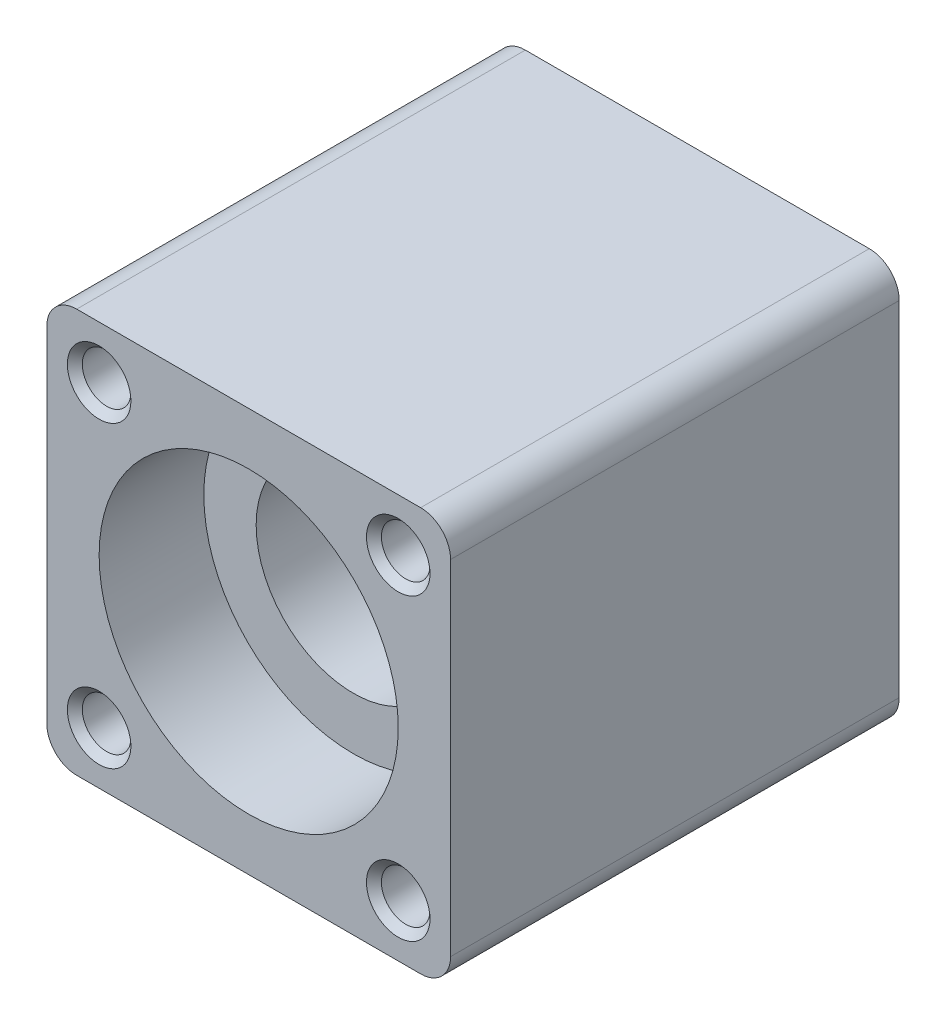
SolidWorks part; units mm, degrees
ref_plane "Alzado" through (0, 0, 0) normal (0, 0, 1) x (1, 0, 0)
ref_plane "Planta" through (0, 0, 0) normal (0, 1, 0) x (1, 0, 0)
ref_plane "Vista lateral" through (0, 0, 0) normal (1, 0, 0) x (0, 0, -1)
sketch "Croquis1" plane through (0, 0, 0) normal (0, 0, 1) x (1, 0, 0)
  line L1 (-27, 27) -> (27, 27)
  line L2 (-27, 27) -> (-27, -27)
  line L3 (-27, -27) -> (27, -27)
  line L4 (27, 27) -> (27, -27)
  line L5 (-27, 27) -> (27, -27) construction
  line L6 (-27, -27) -> (27, 27) construction
  point P0 (0, 0)
  dimension "D1" = 54
  dimension "D2" = 54
extrude "Saliente-Extruir1" add sketch "Croquis1" along normal blind 60
sketch "Croquis2" plane through (0, 0, 60) normal (0, 0, 1) x (1, 0, 0)
  circle A0 centre (0, 0) radius 13
  dimension "D1" = 26
extrude "Cortar-Extruir1" cut sketch "Croquis2" against normal through all
sketch "Croquis3" plane through (0, 0, 60) normal (0, 0, 1) x (1, 0, 0)
  circle A0 centre (0, 0) radius 20
  dimension "D1" = 40
extrude "Cortar-Extruir2" cut sketch "Croquis3" against normal blind 14
sketch "Croquis4" plane through (0, 0, 0) normal (0, 0, -1) x (-1, 0, 0)
  circle A0 centre (0, 0) radius 20
  dimension "D1" = 40
extrude "Cortar-Extruir3" cut sketch "Croquis4" against normal blind 12
sketch "Croquis5" plane through (0, 0, 60) normal (0, 0, 1) x (1, 0, 0)
  line L0 (27, -27) -> (27, 27) construction
  line L1 (27, 27) -> (-27, 27) construction
  circle A0 centre (20, 20) radius 3.25
  circle A1 centre (20, -20) radius 3.25
  circle A2 centre (-20, -20) radius 3.25
  circle A3 centre (-20, 20) radius 3.25
  point P15 (0, 0)
  dimension "D1" = 6.5
  dimension "D2" = 7
  dimension "D3" = 7
  dimension "D4" = 4
extrude "Cortar-Extruir4" cut sketch "Croquis5" against normal through all
fillet "Redondeo1" radius 4 4 edges at (-27, -27, 30) (27, -27, 30) (27, 27, 30) (-27, 27, 30)
chamfer "Chaflán1" distance 1 angle 45 4 edges at (-16.75, -20, 60) (23.25, -20, 60) (23.25, 20, 60) (-16.75, 20, 60)
